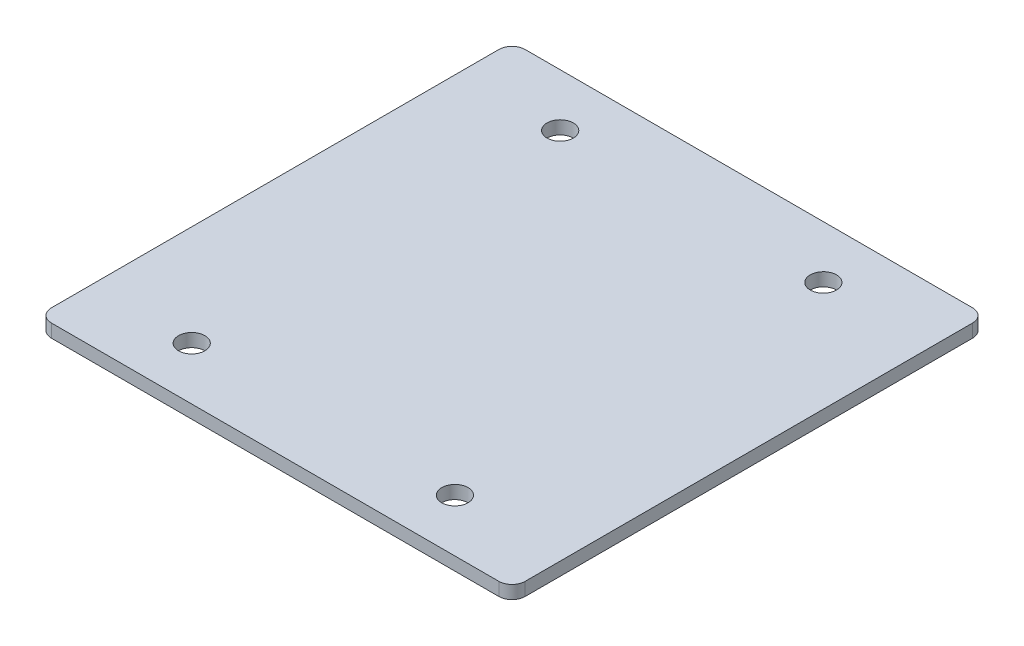
SolidWorks part; units mm, degrees
ref_plane "Front Plane" through (0, 0, 0) normal (0, 0, 1) x (1, 0, 0)
ref_plane "Top Plane" through (0, 0, 0) normal (0, 1, 0) x (1, 0, 0)
ref_plane "Right Plane" through (0, 0, 0) normal (1, 0, 0) x (0, 0, -1)
sketch "Sketch2" plane through (0, 0, 0) normal (0, 1, 0) x (1, 0, 0)
  line L1 (0, 0) -> (114.3, 0)
  line L2 (0, 0) -> (0, 114.3)
  line L3 (0, 114.3) -> (114.3, 114.3)
  line L4 (114.3, 0) -> (114.3, 114.3)
  dimension "D1" = 114.3
  dimension "D2" = 114.3
extrude "Boss-Extrude1" add sketch "Sketch2" along normal blind 3.175
fillet "Fillet1" radius 3.175 4 edges at (114.3, 1.5875, -114.3) (0, 1.5875, -114.3) (0, 1.5875, 0) (114.3, 1.5875, 0)
sketch "Sketch3" plane through (0, 3.175, 0) normal (0, 1, 0) x (1, 0, 0)
  line L0 (57.15, 114.3) -> (57.15, 0) construction
  line L1 (111.125, 114.3) -> (3.175, 114.3) construction
  line L2 (3.175, 0) -> (111.125, 0) construction
  line L4 (114.3, 3.175) -> (114.3, 111.125) construction
  line L5 (114.3, 57.15) -> (0, 57.15) construction
  line L6 (0, 111.125) -> (0, 3.175) construction
  circle A0 centre (24.3229, 101.6) radius 3.175
  circle A1 centre (24.3229, 12.7) radius 3.175
  circle A2 centre (87.8229, 12.7) radius 3.175
  circle A3 centre (87.8229, 101.6) radius 3.175
  dimension "D1" = 6.35
  dimension "D2" = 6.35
  dimension "D3" = 6.35
  dimension "D4" = 6.35
  dimension "D5" = 63.5
  dimension "D6" = 63.5
  dimension "D7" = 12.7
  dimension "D8" = 12.7
extrude "Cut-Extrude1" cut sketch "Sketch3" against normal through all
ref_plane "Plane1" through (57.15, 0, 0) normal (-1, 0, 0) x (0, 0, 1)
